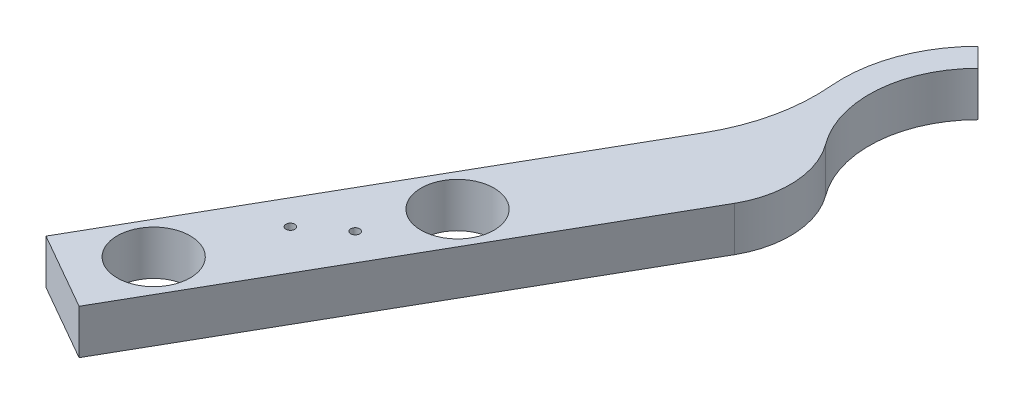
SolidWorks part; units mm, degrees
material "ﾎﾟﾘｴｽﾃﾙ樹脂"
ref_plane "正面" through (0, 0, 0) normal (0, 0, 1) x (1, 0, 0)
ref_plane "平面" through (0, 0, 0) normal (0, 1, 0) x (1, 0, 0)
ref_plane "右側面" through (0, 0, 0) normal (1, 0, 0) x (0, 0, -1)
sketch "ｽｹｯﾁ2" plane through (0, 0, 0) normal (0, 1, 0) x (1, 0, 0)
  line L0 (24.4315, 35.0023) -> (24.4315, 50035.0023) construction
  line L5 (0, 0) -> (-15.8798, -27.754) construction
  line L7 (-20.2196, -25.2709) -> (11.5399, 30.2371)
  line L10 (-20.2196, -25.2709) -> (-11.5399, -30.2371)
  line L11 (11.5399, 30.2371) -> (20.2196, 25.2709)
  line L14 (-11.5399, -30.2371) -> (20.2196, 25.2709)
  line L18 (-20.2196, -25.2709) -> (20.2196, 25.2709) construction
  line L19 (11.5399, 30.2371) -> (-11.5399, -30.2371) construction
  line L20 (20.2196, 25.2709) -> (18.5739, 22.3945)
  line L21 (20.2196, 25.2709) -> (18.5739, 22.3945)
  line L22 (18.5739, 22.3945) -> (24.4315, 34.7237) construction
  line L26 (13.6481, 45.5071) -> (35.2149, 23.9404)
  line L27 (0, 0) -> (15.8798, 27.754) construction
  circle A9 centre (24.4315, 34.7237) radius 12.225
  circle A10 centre (24.4315, 34.7237) radius 13.65
  circle A11 centre (24.4315, 34.7237) radius 15.25
  circle A12 centre (-12.1551, -21.2442) radius 4.1
  circle A13 centre (0.2603, 0.455) radius 4.1
  point P6 (0, 0)
  dimension "D2" = 63.9516
  dimension "D4" = 27.3
  dimension "D7" = 30.5
  dimension "D8" = 4.2119
  dimension "D9" = 7.5
  dimension "D10" = 8.2
  dimension "D3" = 24.45
  dimension "D11" = 25
  dimension "D1" = 10
  dimension "D5" = 45
  dimension "D6" = 150.223
extrude "ﾎﾞｽ - 押し出し1" add sketch "ｽｹｯﾁ2" along normal blind 5
fillet "ﾌｨﾚｯﾄ1" radius 20 1 edges at (10.5254, 2.5, -28.464)
sketch "ｽｹｯﾁ6" plane through (0, 5, 0) normal (0, 1, 0) x (1, 0, 0)
  circle A0 centre (-7.4087, -10.6393) radius 0.5
  circle A1 centre (-3.3295, -7.4444) radius 0.5
  dimension "D1" = 1
extrude "ｶｯﾄ - 押し出し3" cut sketch "ｽｹｯﾁ6" against normal through all
fillet "ﾌｨﾚｯﾄ2" radius 10 1 edges at (19.2838, 2.5, -23.6354)
